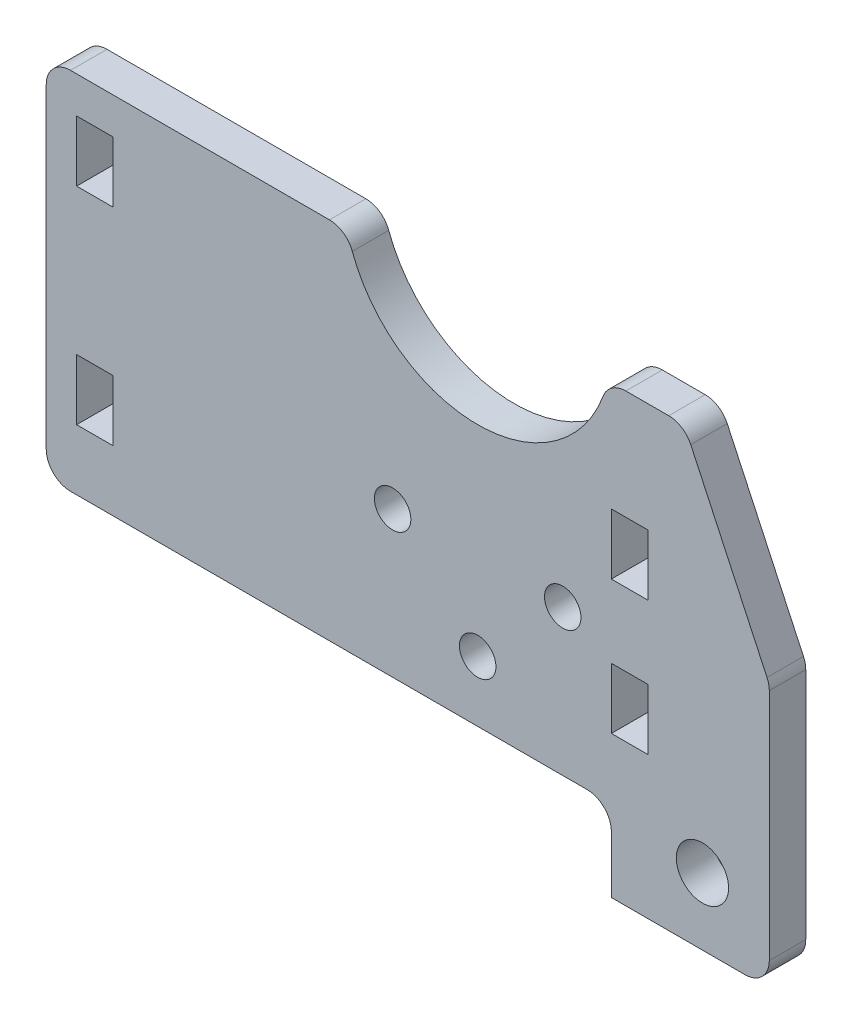
SolidWorks part; units mm, degrees
ref_plane "Front Plane" through (0, 0, 0) normal (0, 0, 1) x (1, 0, 0)
ref_plane "Top Plane" through (0, 0, 0) normal (0, 1, 0) x (1, 0, 0)
ref_plane "Right Plane" through (0, 0, 0) normal (1, 0, 0) x (0, 0, -1)
sketch "草图1" plane through (0, 0, 0) normal (0, 0, 1) x (1, 0, 0)
  line L1 (-26, -15) -> (26, -15)
  line L2 (-26, -15) -> (-26, 15)
  line L3 (-26, 15) -> (26, 15)
  line L4 (26, -15) -> (26, 15)
  line L5 (-26, -15) -> (26, 15) construction
  line L6 (-26, 15) -> (26, -15) construction
  point P0 (0, 0)
  dimension "D1" = 30
  dimension "D2" = 52
extrude "凸台-拉伸1" add sketch "草图1" along normal blind 3
sketch "草图2" plane through (0, 0, 3) normal (0, 0, 1) x (1, 0, 0)
  line L0 (0, 23.231) -> (0, -23.2713) construction
  line L1 (23.5, 27.0014) -> (23.5, -24.4496) construction
  line L2 (26, -15) -> (26, 15) construction
  line L3 (-29.6284, 0) -> (37.0615, 0) construction
  line L4 (-26, -15) -> (26, -15) construction
  line L5 (23.5, -5) -> (20.5, -5)
  line L6 (23.5, -5) -> (23.5, -10)
  line L7 (23.5, -10) -> (20.5, -10)
  line L8 (20.5, -5) -> (20.5, -10)
  line L9 (23.5, -5) -> (20.5, -10) construction
  line L10 (23.5, -10) -> (20.5, -5) construction
  line L11 (23.5, 12) -> (20.5, 12)
  line L12 (23.5, 12) -> (23.5, 7)
  line L13 (23.5, 7) -> (20.5, 7)
  line L14 (20.5, 12) -> (20.5, 7)
  line L15 (23.5, 12) -> (20.5, 7) construction
  line L16 (23.5, 7) -> (20.5, 12) construction
  line L17 (-23.5, 7) -> (-20.5, 12) construction
  line L18 (-23.5, 12) -> (-20.5, 7) construction
  line L19 (-23.5, -10) -> (-20.5, -5) construction
  line L20 (-23.5, -5) -> (-20.5, -10) construction
  line L21 (-20.5, 12) -> (-20.5, 7)
  line L22 (-23.5, 7) -> (-20.5, 7)
  line L23 (-23.5, 12) -> (-23.5, 7)
  line L24 (-23.5, 12) -> (-20.5, 12)
  line L25 (-20.5, -5) -> (-20.5, -10)
  line L26 (-23.5, -10) -> (-20.5, -10)
  line L27 (-23.5, -5) -> (-23.5, -10)
  line L28 (-23.5, -5) -> (-20.5, -5)
  point P13 (22, -7.5)
  point P18 (22, 9.5)
  point P29 (-22, 9.5)
  point P30 (-22, -7.5)
  dimension "D1" = 2.5
  dimension "D2" = 3
  dimension "D3" = 3
  dimension "D4" = 5
  dimension "D5" = 5
  dimension "D6" = 12
  dimension "D7" = 5
extrude "切除-拉伸1" cut sketch "草图2" against normal blind 4
sketch "草图6" plane through (0, 0, 0) normal (0, 0, -1) x (-1, 0, 0)
  line L1 (-24.1777, 12.7083) -> (-19.5538, 12.7083)
  line L2 (-24.1777, 12.7083) -> (-24.1777, 6.3305)
  line L3 (-24.1777, 6.3305) -> (-19.5538, 6.3305)
  line L4 (-19.5538, 12.7083) -> (-19.5538, 6.3305)
  line L5 (-24.1777, 12.7083) -> (-19.5538, 6.3305) construction
  line L6 (-24.1777, 6.3305) -> (-19.5538, 12.7083) construction
  point P4 (-21.8658, 9.5194)
extrude "凸台-拉伸2" add sketch "草图6" against normal up to surface (3 mm away) up to face at (-22, -7.5, 3)
sketch "草图7" plane through (0, 0, 0) normal (0, 0, -1) x (-1, 0, 0)
  line L1 (-23.5, 1) -> (-20.5, 1)
  line L2 (-23.5, 1) -> (-23.5, 6)
  line L3 (-23.5, 6) -> (-20.5, 6)
  line L4 (-20.5, 1) -> (-20.5, 6)
  line L5 (-23.5, 1) -> (-20.5, 6) construction
  line L6 (-23.5, 6) -> (-20.5, 1) construction
  line L7 (-23.5, -5) -> (-23.5, -10) construction
  line L8 (-20.5, -5) -> (-23.5, -5) construction
  point P4 (-22, 3.5)
  dimension "D1" = 3
  dimension "D2" = 5
  dimension "D3" = 6
extrude "切除-拉伸4" cut sketch "草图7" against normal blind 10
sketch "草图9" plane through (0, 0, 3) normal (0, 0, 1) x (1, 0, 0)
  line L0 (26, -15) -> (26, 15) construction
  line L1 (-26, -15) -> (26, -15) construction
  line L2 (23.5, -10) -> (23.5, -15) construction
  line L3 (26, 15) -> (31.495, 15)
  line L4 (31.495, 15) -> (31.495, -21.695)
  line L5 (31.495, -21.695) -> (20.5, -21.695)
  line L6 (20.5, -21.695) -> (20.5, -15)
  line L7 (20.5, -5) -> (20.5, -10) construction
  line L8 (20.5, -15) -> (26, -15)
  line L9 (26, -15) -> (26, 15)
  circle A0 centre (27.995, -16.195) radius 2
  dimension "D1" = 4
  dimension "D2" = 1.995
  dimension "D3" = 1.195
  dimension "D4" = 3.5
  dimension "D5" = 5.5
extrude "凸台-拉伸3" add sketch "草图9" against normal up to surface (3 mm away) up to face at (22, 3.5, 0)
sketch "草图10" plane through (0, 0, 3) normal (0, 0, 1) x (1, 0, 0)
  circle A0 centre (27.995, -16.195) radius 2.25
  dimension "D1" = 4.5
extrude "切除-拉伸5" cut sketch "草图10" against normal blind 10
sketch "草图11" plane through (0, 0, 3) normal (0, 0, 1) x (1, 0, 0)
  line L0 (2.5, -3) -> (16.5, -3) construction
  line L1 (20.5, -5) -> (20.5, -10) construction
  line L2 (-26, -15) -> (20.5, -15) construction
  circle A0 centre (2.5, -3) radius 1.5
  circle A1 centre (16.5, -3) radius 1.5
  circle A2 centre (9.5, -10) radius 1.5
  dimension "D1" = 3
  dimension "D2" = 3
  dimension "D3" = 14
  dimension "D4" = 3
  dimension "D5" = 7
  dimension "D6" = 7
  dimension "D7" = 11
  dimension "D8" = 5
extrude "切除-拉伸6" cut sketch "草图11" against normal blind 10
sketch "草图12" plane through (0, 0, 3) normal (0, 0, 1) x (1, 0, 0)
  line L0 (2.5, -3) -> (16.5, -3) construction
  line L1 (9.5, 22.3242) -> (9.5, -19.4216) construction
  line L2 (31.495, 15) -> (-26, 15) construction
  circle A0 centre (16.5, -3) radius 1.5 construction
  circle A1 centre (2.5, -3) radius 1.5 construction
  circle A2 centre (9.5, 17.5) radius 11
  dimension "D1" = 22
  dimension "D2" = 2.5
extrude "切除-拉伸7" cut sketch "草图12" against normal blind 10
fillet "圆角1" radius 2 3 edges at (-1.2121, 15, 1.5) (20.2121, 15, 1.5) (20.5, -15, 1.5)
sketch "草图13" plane through (0, 0, 3) normal (0, 0, 1) x (1, 0, 0)
  line L0 (31.495, 15) -> (33.495, 15)
  line L1 (33.495, 15) -> (33.495, -21.695)
  line L2 (33.495, -21.695) -> (31.495, -21.695)
  line L3 (20.5, -21.695) -> (31.495, -21.695) construction
  line L4 (31.495, 15) -> (31.495, -21.695)
  dimension "D1" = 2
extrude "凸台-拉伸4" add sketch "草图13" against normal up to surface (3 mm away) up to face at (9.9004, -0.8358, 0)
fillet "圆角2" radius 2 1 edges at (33.495, -21.695, 1.5)
chamfer "倒角1" distance 7 angle 65 1 edges at (33.495, 15, 1.5)
fillet "圆角3" radius 2 2 edges at (33.495, -0.0115, 1.5) (26.495, 15, 1.5)
sketch "草图15" plane through (0, 0, 3) normal (0, 0, 1) x (1, 0, 0)
  circle A0 centre (27.995, -16.195) radius 2.25
  circle A1 centre (27.995, -16.195) radius 2.15
  dimension "D1" = 4.5
  dimension "D2" = 4.3
extrude "凸台-拉伸6" add sketch "草图15" against normal up to surface (3 mm away) up to face at (15.3727, -1.0166, 0)
fillet "圆角4" radius 2 2 edges at (-26, -15, 1.5) (-26, 15, 1.5)
